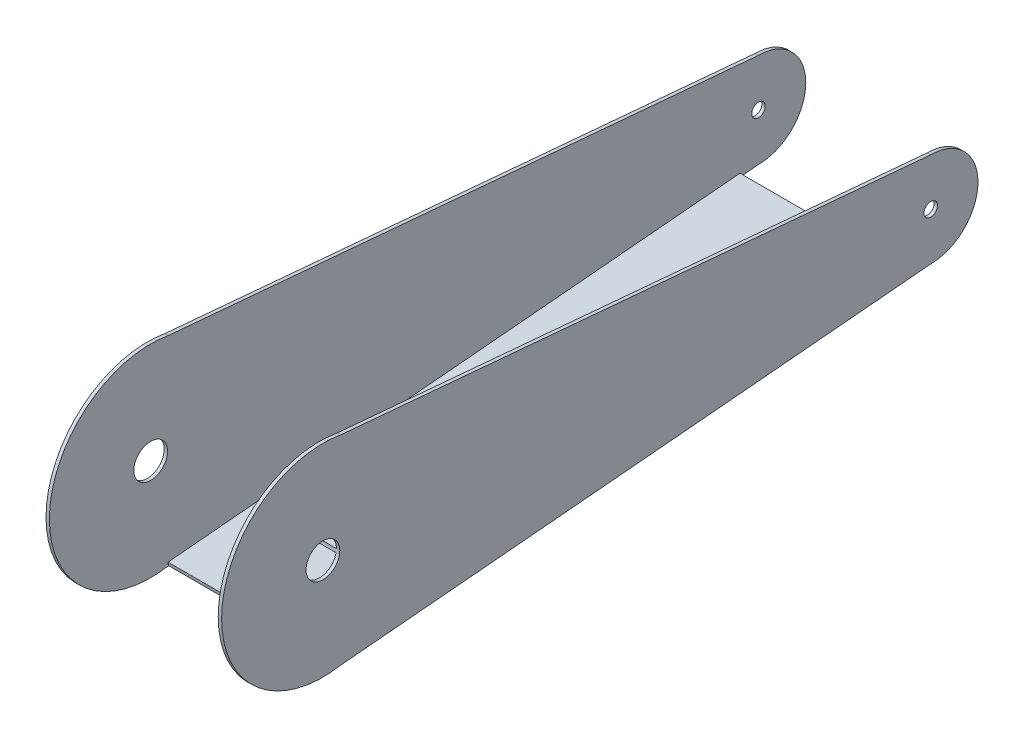
SolidWorks part; units mm, degrees
ref_plane "Front Plane" through (0, 0, 0) normal (0, 0, 1) x (1, 0, 0)
ref_plane "Top Plane" through (0, 0, 0) normal (0, 1, 0) x (1, 0, 0)
ref_plane "Right Plane" through (0, 0, 0) normal (1, 0, 0) x (0, 0, -1)
sketch "Sketch1" plane through (0, 0, 0) normal (1, 0, 0) x (0, 0, -1)
  line L0 (5.2915, 29.5296) -> (180, 14)
  line L2 (180, -14) -> (5.2915, -29.5296)
  arc A0 (5.2915, 29.5296) -> (5.2915, -29.5296) centre (0, 0) ccw
  arc A1 (180, -14) -> (180, 14) centre (180, 0) ccw
  circle A2 centre (0, 0) radius 5
  circle A3 centre (180, 0) radius 2.5
  dimension "D1" = 180
  dimension "D2" = 28
  dimension "D3" = 60
  dimension "D4" = 5
  dimension "D5" = 10
extrude "Boss-Extrude1" add sketch "Sketch1" along normal mid plane 52 contours L0 A1 L2 A0 | A2 | A3
sketch "Sketch2" plane through (0, 0, 0) normal (1, 0, 0) x (0, 0, -1)
  line L0 (5.2915, -29.5296) -> (5.1144, -28.5414)
  line L1 (180, -14) -> (174.5951, -14.4804)
  line L4 (174.5065, -13.4844) -> (5.1144, -28.5414)
  line L5 (5.2915, 29.5296) -> (180, 14) construction
  line L6 (5.2915, 29.5296) -> (180, 14)
  line L8 (180, -14) -> (5.2915, -29.5296) construction
  line L9 (174.5951, -14.4804) -> (174.5065, -13.4844)
  arc A8 (180, -14) -> (180, 14) centre (180, 0) ccw construction
  arc A9 (5.2915, 29.5296) -> (5.2915, -29.5296) centre (0, 0) ccw construction
  arc A10 (180, -14) -> (180, 14) centre (180, 0) ccw
  arc A11 (5.2915, 29.5296) -> (5.2915, -29.5296) centre (0, 0) ccw
extrude "Cut-Extrude1" cut sketch "Sketch2" against normal mid plane 50
sketch "Sketch4" plane through (-26, 0, 0) normal (-1, 0, 0) x (0, 0, 1)
  circle A0 centre (-180, 0) radius 2.5
sketch "Sketch5" plane through (-26, 0, 0) normal (-1, 0, 0) x (0, 0, 1)
  circle A0 centre (-180, 0) radius 2
  circle A1 centre (-180, 0) radius 2.6747
  dimension "D1" = 4
extrude "Boss-Extrude2" add sketch "Sketch5" against normal up to surface (1 mm away) up to face at (-25, 0, -5)
sketch "Sketch6" plane through (26, 0, 0) normal (1, 0, 0) x (0, 0, -1)
  circle A0 centre (180, 0) radius 2.5
  circle A1 centre (180, 0) radius 2
  dimension "D1" = 4
extrude "Boss-Extrude3" add sketch "Sketch6" against normal up to surface (1 mm away) up to face at (25, 0, -5)
sketch "Sketch7" plane through (25, 0, 0) normal (-1, 0, 0) x (0, 0, 1)
  line L0 (0, 0) -> (-180, 0)
  line L1 (-180, 0) -> (0, 0)
  line L2 (-180, 0) -> (-180, -1)
  line L3 (0, 0) -> (0, -1)
  line L4 (-180, -1) -> (0, -1)
  circle M4 centre (0, 0) radius 5
  circle M12 centre (-180, 0) radius 2
  dimension "D1" = 1
extrude "Boss-Extrude4" add sketch "Sketch7" along normal blind 5 contours L4 L0 M12 M4
